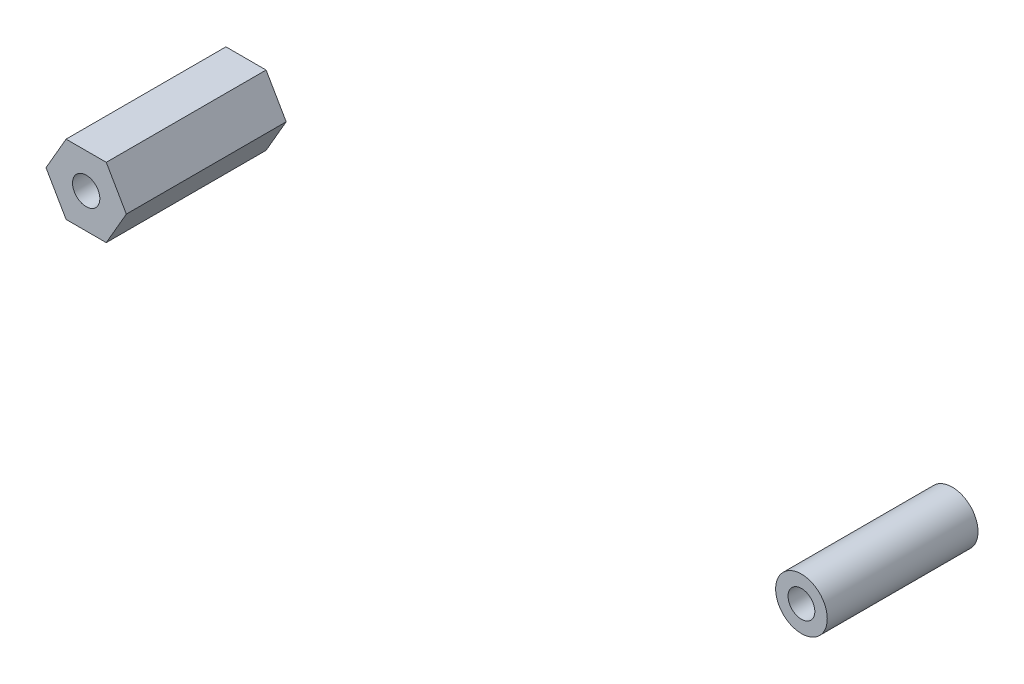
SolidWorks part; units mm, degrees
ref_plane "Front Plane" through (0, 0, 0) normal (0, 0, 1) x (1, 0, 0)
ref_plane "Top Plane" through (0, 0, 0) normal (0, 1, 0) x (1, 0, 0)
ref_plane "Right Plane" through (0, 0, 0) normal (1, 0, 0) x (0, 0, -1)
sketch "Sketch1" plane through (0, 0, 0) normal (0, 0, 1) x (1, 0, 0)
  line L0 (-38.3303, 17.78) -> (-40.7551, 21.98)
  line L1 (-41.5057, 20.68) -> (-44.8543, 20.68)
  line L2 (-44.8543, 20.68) -> (-46.5286, 17.78)
  line L3 (-46.5286, 17.78) -> (-44.8543, 14.88)
  line L4 (-44.8543, 14.88) -> (-41.5057, 14.88)
  line L5 (-41.5057, 14.88) -> (-39.8314, 17.78)
  line L6 (-39.8314, 17.78) -> (-41.5057, 20.68)
  line L7 (-40.7551, 21.98) -> (-45.6049, 21.98)
  line L8 (-45.6049, 21.98) -> (-48.0297, 17.78)
  line L9 (-48.0297, 17.78) -> (-45.6049, 13.58)
  line L10 (-45.6049, 13.58) -> (-40.7551, 13.58)
  line L11 (-40.7551, 13.58) -> (-38.3303, 17.78)
  circle A0 centre (-43.18, 17.78) radius 1.5 construction
  circle A1 centre (-43.18, 17.78) radius 1.5 construction
  circle A2 centre (-43.18, 17.78) radius 2.9 construction
  dimension "D1" = 5.8
  dimension "D2" = 1.3
extrude "Boss-Extrude1" add sketch "Sketch1" along normal blind 2.5
sketch "Sketch2" plane through (0, 0, 2.5) normal (0, 0, 1) x (1, 0, 0)
  line L6 (-40.7551, 13.58) -> (-38.3303, 17.78)
  line L7 (-38.3303, 17.78) -> (-40.7551, 21.98)
  line L8 (-40.7551, 21.98) -> (-45.6049, 21.98)
  line L9 (-45.6049, 21.98) -> (-48.0297, 17.78)
  line L10 (-48.0297, 17.78) -> (-45.6049, 13.58)
  line L11 (-45.6049, 13.58) -> (-40.7551, 13.58)
  line L12 (-40.7551, 13.58) -> (-38.3303, 17.78)
  line L13 (-38.3303, 17.78) -> (-40.7551, 21.98)
  line L14 (-40.7551, 21.98) -> (-45.6049, 21.98)
  line L15 (-45.6049, 21.98) -> (-48.0297, 17.78)
  line L16 (-48.0297, 17.78) -> (-45.6049, 13.58)
  line L17 (-45.6049, 13.58) -> (-40.7551, 13.58)
  circle A0 centre (-43.18, 17.78) radius 1.65
  dimension "D1" = 3.3
  dimension "D2" = 0
extrude "Boss-Extrude2" add sketch "Sketch2" along normal offset from surface (19.3 mm away) 0.1
sketch "Sketch3" plane through (0, 0, 21.8) normal (0, 0, 1) x (1, 0, 0)
  circle A0 centre (43.18, 17.78) radius 1.5 construction
  circle A1 centre (43.18, 17.78) radius 1.5 construction
  circle A2 centre (43.18, 17.78) radius 1.6165
  circle A3 centre (43.18, 17.78) radius 3.1165
  dimension "D1" = 3.233
  dimension "D2" = 1.5
extrude "Boss-Extrude3" add sketch "Sketch3" against normal offset from surface (18.2 mm away) 2.6 separate body
sketch "Sketch4" plane through (0, 0, 0) normal (0, 0, -1) x (-1, 0, 0)
  line L6 (38.3303, 17.78) -> (40.7551, 13.58)
  line L7 (40.7551, 13.58) -> (45.6049, 13.58)
  line L8 (45.6049, 13.58) -> (48.0297, 17.78)
  line L9 (48.0297, 17.78) -> (45.6049, 21.98)
  line L10 (45.6049, 21.98) -> (40.7551, 21.98)
  line L11 (40.7551, 21.98) -> (38.3303, 17.78)
  line L12 (38.3303, 17.78) -> (40.7551, 13.58)
  line L13 (40.7551, 13.58) -> (45.6049, 13.58)
  line L14 (45.6049, 13.58) -> (48.0297, 17.78)
  line L15 (48.0297, 17.78) -> (45.6049, 21.98)
  line L16 (45.6049, 21.98) -> (40.7551, 21.98)
  line L17 (40.7551, 21.98) -> (38.3303, 17.78)
  dimension "D1" = 0
extrude "Cut-Extrude1" cut sketch "Sketch4" against normal up to surface (2.5 mm away) up to face at (-43.18, 17.78, 2.5)
